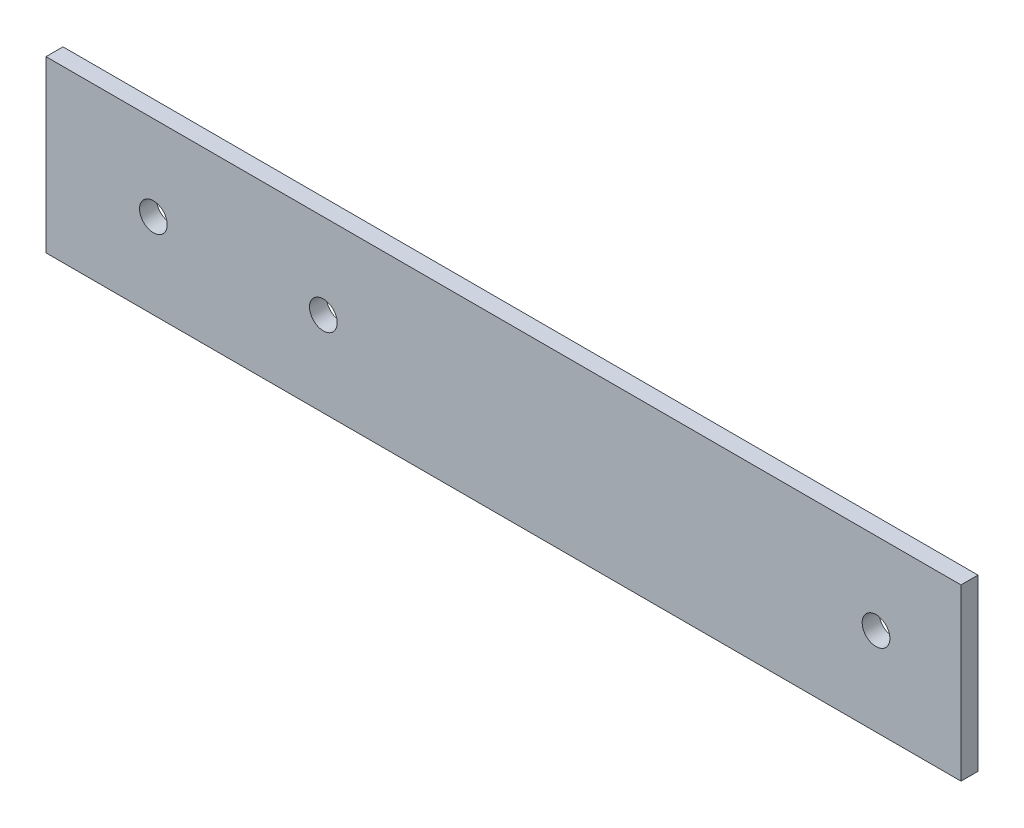
SolidWorks part; units mm, degrees
ref_plane "Front" through (0, 0, 0) normal (0, 0, 1) x (1, 0, 0)
ref_plane "Top" through (0, 0, 0) normal (0, 1, 0) x (1, 0, 0)
ref_plane "Right" through (0, 0, 0) normal (1, 0, 0) x (0, 0, -1)
sketch "Sketch1" plane through (0, 0, 0) normal (0, 0, 1) x (1, 0, 0)
  line L9 (17.7896, 202.3011) -> (17.7896, 176.9011)
  line L10 (17.7896, 176.9011) -> (-118.9384, 176.9011)
  line L11 (-118.9384, 176.9011) -> (-118.9384, 202.3011)
  line L13 (-118.9384, 202.3011) -> (17.7896, 202.3011)
  circle A0 centre (5.0896, 190.0427) radius 2.0701
  arc A1 (3.0209, 189.9665) -> (7.1583, 189.9665) centre (5.0896, 190.0427) ccw construction
  circle A2 centre (-77.4929, 189.6011) radius 2.0701
  circle A3 centre (-102.8929, 189.6011) radius 2.0701
  arc A4 (-100.8242, 189.6773) -> (-104.9616, 189.6773) centre (-102.8929, 189.6011) ccw construction
  arc A5 (-75.4242, 189.6773) -> (-79.5616, 189.6773) centre (-77.4929, 189.6011) ccw construction
  point P0 (0, 0)
  point P1 (0, 0)
  dimension "D1" = 25.4
extrude "Boss-Extrude1" add sketch "Sketch1" along normal blind 2.54
sketch "Bend-Lines1" [suppressed] plane through (0, 0, 0) normal (0, 1, 0) x (1, 0, 0)
sketch "Bounding-Box1" [suppressed] plane through (0, 0, 0) normal (0, 1, 0) x (1, 0, 0)
